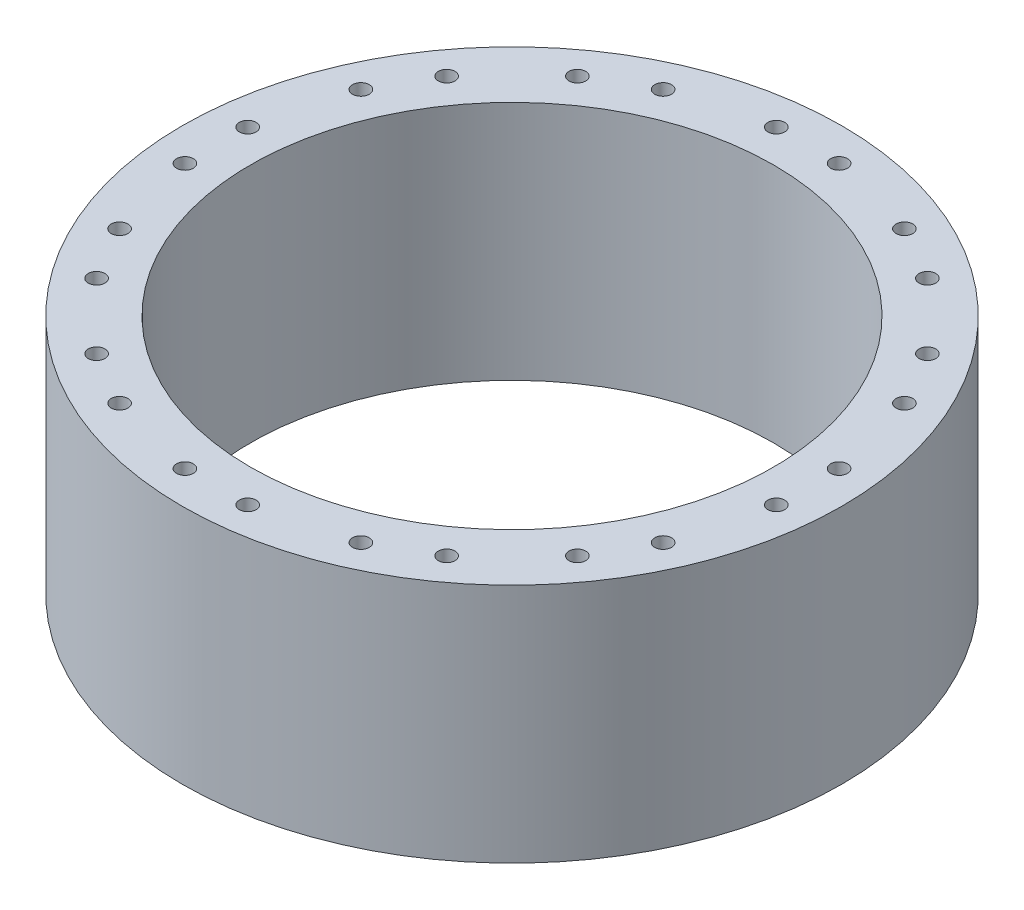
SolidWorks part; units mm, degrees
material "2024-T4"
ref_plane "Front Plane" through (0, 0, 0) normal (0, 0, 1) x (1, 0, 0)
ref_plane "Top Plane" through (0, 0, 0) normal (0, 1, 0) x (1, 0, 0)
ref_plane "Right Plane" through (0, 0, 0) normal (1, 0, 0) x (0, 0, -1)
sketch "Sketch1" plane through (0, 0, 0) normal (0, 1, 0) x (1, 0, 0)
  circle A0 centre (0, 0) radius 157.5
  circle A1 centre (0, 0) radius 125
  dimension "D1" = 315
  dimension "D2" = 250
extrude "Boss-Extrude1" add sketch "Sketch1" against normal blind 10 and the other way blind 105
sketch "Sketch3" plane through (0, -10, 0) normal (0, -1, 0) x (-1, 0, 0)
  line L0 (0, -680) -> (0, 49320) construction
  line L1 (-866.0254, 500) -> (42435.2448, -24500) construction
  line L2 (-866.0254, -500) -> (42435.2448, 24500) construction
  line L3 (-500, -866.0254) -> (24500, 42435.2448) construction
  line L4 (-500, 866.0254) -> (24500, -42435.2448) construction
  line L5 (-1000, 0) -> (49000, 0) construction
  circle A0 centre (0, 0) radius 125 construction
  circle A2 centre (0, 0) radius 157.5 construction
  circle A4 centre (0, 0) radius 157.5 construction
  circle A5 centre (-15, 141.25) radius 4
  circle A6 centre (15, 141.25) radius 4
  point P3 (0, 125)
  point P6 (0, 157.5)
  point P21 (-125, 0)
  point P24 (-108.2532, 62.5)
  point P25 (-157.5, 0)
  point P26 (-136.399, 78.75)
  dimension "D3" = 30
  dimension "D1" = 30
  dimension "D2" = 8
  dimension "D4" = 64.7048
  dimension "D5" = 81.528
  dimension "D6" = 157.5
  dimension "D7" = 16.25
extrude "Cut-Extrude2" cut sketch "Sketch3" against normal through all
pattern_circular "CirPattern2" count 12 over 360 about axis through (0, 0, 0) along (0, 1, 0) of "Cut-Extrude2"
